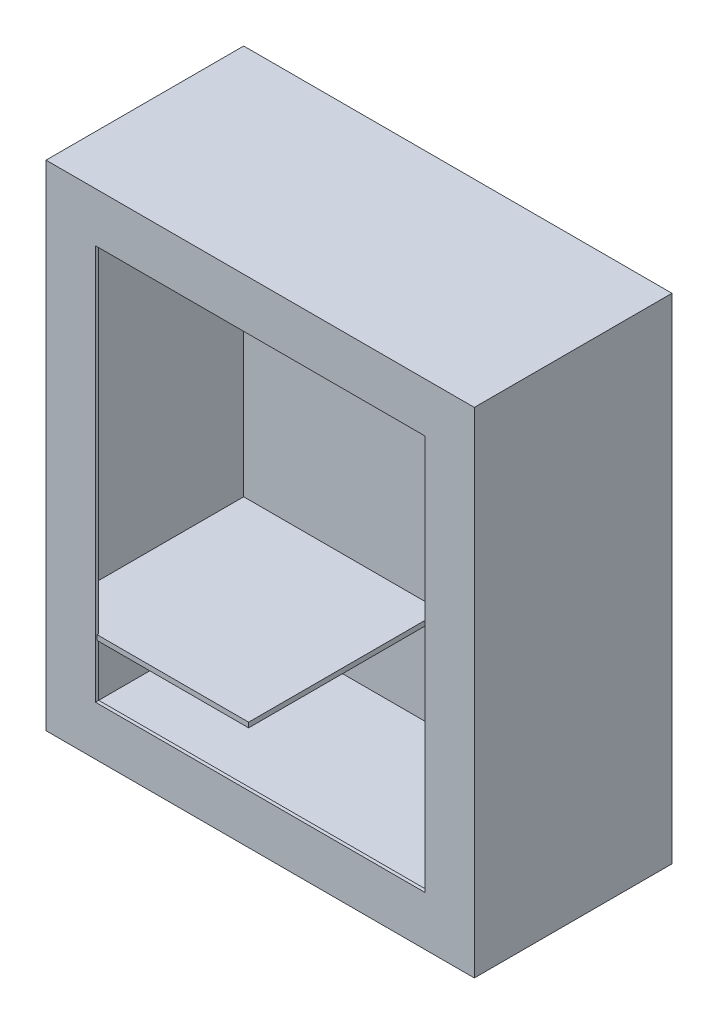
SolidWorks part; units mm, degrees
ref_plane "Alzado" through (0, 0, 0) normal (0, 0, 1) x (1, 0, 0)
ref_plane "Planta" through (0, 0, 0) normal (0, 1, 0) x (1, 0, 0)
ref_plane "Vista lateral" through (0, 0, 0) normal (1, 0, 0) x (0, 0, -1)
sketch "Croquis2" plane through (0, 0, 0) normal (0, 0, 1) x (1, 0, 0)
  line L1 (130, 150) -> (-130, 150)
  line L2 (130, 150) -> (130, -150)
  line L3 (130, -150) -> (-130, -150)
  line L4 (-130, 150) -> (-130, -150)
  line L5 (130, 150) -> (-130, -150) construction
  line L6 (130, -150) -> (-130, 150) construction
  point P0 (0, 0)
  dimension "D1" = 260
  dimension "D2" = 300
extrude "Saliente-Extruir1" add sketch "Croquis2" along normal blind 120
sketch "Croquis3" plane through (0, 0, 120) normal (0, 0, 1) x (1, 0, 0)
  line L1 (100, 120) -> (-100, 120)
  line L2 (100, 120) -> (100, -120)
  line L3 (100, -120) -> (-100, -120)
  line L4 (-100, 120) -> (-100, -120)
  line L5 (100, 120) -> (-100, -120) construction
  line L6 (100, -120) -> (-100, 120) construction
  point P0 (0, 0)
  dimension "D1" = 200
  dimension "D2" = 240
extrude "Cortar-Extruir2" cut sketch "Croquis3" against normal blind 2
sketch "Croquis4" plane through (0, 0, 118) normal (0, 0, 1) x (1, 0, 0)
  line L1 (128, 148) -> (-128, 148)
  line L2 (128, 148) -> (128, -148)
  line L3 (128, -148) -> (-128, -148)
  line L4 (-128, 148) -> (-128, -148)
  line L5 (128, 148) -> (-128, -148) construction
  line L6 (128, -148) -> (-128, 148) construction
  point P0 (0, 0)
  dimension "D1" = 256
  dimension "D2" = 296
extrude "Cortar-Extruir3" cut sketch "Croquis4" against normal blind 116
sketch "Croquis5" plane through (0, 0, 120) normal (0, 0, 1) x (1, 0, 0)
  line L0 (-100, 120) -> (-130, 150)
  line L1 (100, 120) -> (130, 150)
  line L2 (100, -120) -> (130, -150)
  line L3 (-130, -150) -> (-100, -120)
sketch "Croquis6" plane through (-128, 0, 0) normal (1, 0, 0) x (0, 0, -1)
  line L0 (-2, 148) -> (-2, -148) construction
  line L1 (-2, -85) -> (-119, -85)
  line L2 (-2, -85) -> (-2, -88)
  line L3 (-2, -88) -> (-119, -88)
  line L4 (-119, -85) -> (-119, -88)
  line L5 (-2, -148) -> (-118, -148) construction
  dimension "D1" = 117
  dimension "D2" = 3
  dimension "D3" = 60
extrude "Saliente-Extruir2" add sketch "Croquis6" along normal blind 120
